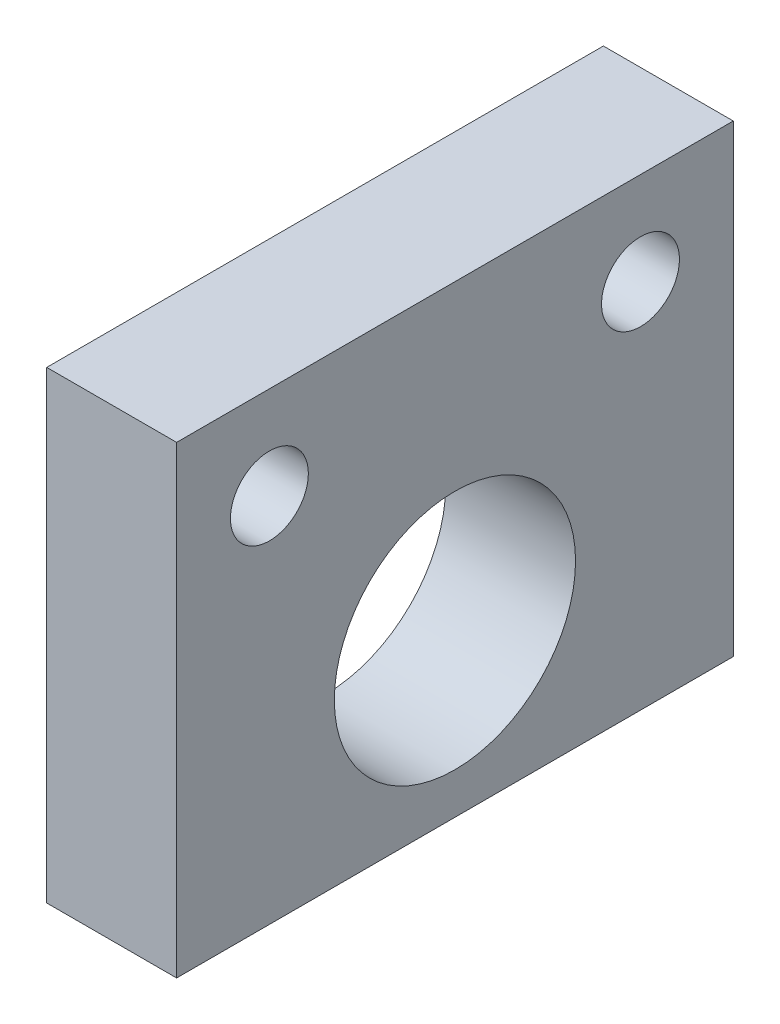
SolidWorks part; units mm, degrees
ref_plane "Front Plane" through (0, 0, 0) normal (0, 0, 1) x (1, 0, 0)
ref_plane "Top Plane" through (0, 0, 0) normal (0, 1, 0) x (1, 0, 0)
ref_plane "Right Plane" through (0, 0, 0) normal (1, 0, 0) x (0, 0, -1)
sketch "Sketch2" plane through (0, 0, 0) normal (0, 1, 0) x (1, 0, 0)
  line L1 (-3.5, -15) -> (3.5, -15)
  line L2 (-3.5, -15) -> (-3.5, 15)
  line L3 (-3.5, 15) -> (3.5, 15)
  line L4 (3.5, -15) -> (3.5, 15)
  line L5 (-3.5, -15) -> (3.5, 15) construction
  line L6 (-3.5, 15) -> (3.5, -15) construction
  point P0 (0, 0)
  dimension "D1" = 30
  dimension "D2" = 7
extrude "Boss-Extrude1" add sketch "Sketch2" along normal blind 25
sketch "Sketch5" plane through (3.5, 0, 0) normal (1, 0, 0) x (0, 0, -1)
  line L1 (-15, 25) -> (15, 25) construction
  circle A0 centre (0, 8.72) radius 6.5
  dimension "D1" = 13
  dimension "D2" = 16.28
extrude "Cut-Extrude1" cut sketch "Sketch5" against normal up to surface (7 mm away) up to face at (-3.5, 12.5, 0)
sketch "Sketch6" plane through (3.5, 0, 0) normal (1, 0, 0) x (0, 0, -1)
  line L0 (-16.6356, 20) -> (21.1592, 20) construction
  line L1 (-15, 25) -> (15, 25) construction
  point P4 (-10, 20)
  point P6 (10, 20)
  dimension "D1" = 5
  dimension "D2" = 10
  dimension "D3" = 10
hole_wizard "M5x0.8 Tapped Hole2" positions "Sketch6" profile "Sketch7" tap size "M5x0.8" standard "ANSI Metric" end condition through all
sketch "Sketch7" plane through (3.5, 20, -10) normal (0, 1, 0) x (0, 0, -1)
  line L0 (0, 0) -> (0, 7)
  line L1 (0, 7) -> (2.1, 7)
  line L2 (2.1, 7) -> (2.1, 0)
  line L5 (2.1, 0) -> (0, 0)
  line L11 (0, -6.35) -> (0, 107.95) construction
  dimension "Thru Tap Drill Dia." = 4.2
  dimension "Thru Tap Drill Depth" = 7
cosmetic thread "Hole Thread2" parameters "D2"=5
cosmetic thread "Hole Thread3" parameters "D2"=5
